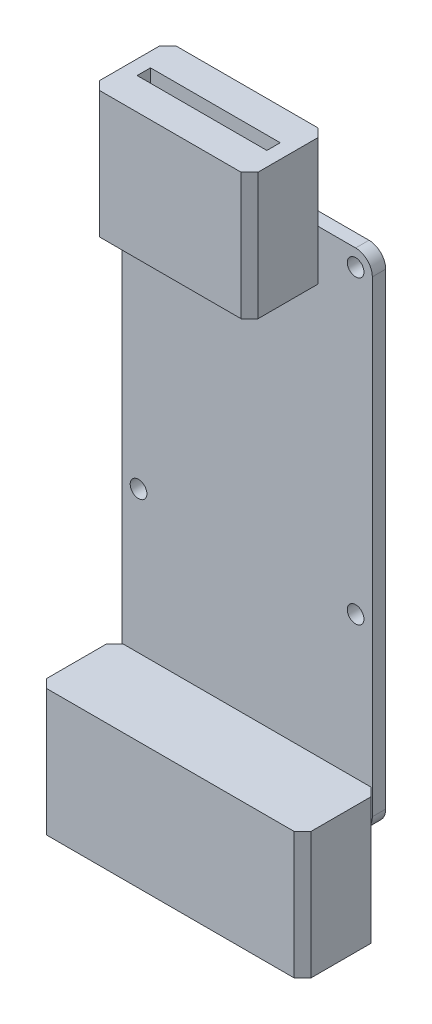
SolidWorks part; units mm, degrees
ref_plane "前视基准面" through (0, 0, 0) normal (0, 0, 1) x (1, 0, 0)
ref_plane "上视基准面" through (0, 0, 0) normal (0, 1, 0) x (1, 0, 0)
ref_plane "右视基准面" through (0, 0, 0) normal (1, 0, 0) x (0, 0, -1)
other "Configuration Table"
sketch "草图1" plane through (0, 0, 0) normal (0, 0, 1) x (1, 0, 0)
  line L1 (-13, 32.5) -> (13, 32.5)
  line L2 (-15, 30.5) -> (-15, -25.5)
  line L3 (-13, -27.5) -> (13, -27.5)
  line L4 (15, 30.5) -> (15, -25.5)
  arc A0 (-13, 32.5) -> (-15, 30.5) centre (-13, 30.5) ccw
  arc A1 (15, 30.5) -> (13, 32.5) centre (13, 30.5) ccw
  circle A2 centre (-13, 30.5) radius 1
  circle A3 centre (13, 30.5) radius 1
  arc A4 (-15, -25.5) -> (-13, -27.5) centre (-13, -25.5) ccw
  arc A5 (13, -27.5) -> (15, -25.5) centre (13, -25.5) ccw
  point P0 (0, 0)
  dimension "D3" = 4
  dimension "D4" = 4
  dimension "D5" = 2
  dimension "D6" = 2
  dimension "D7" = 4
  dimension "D8" = 4
  dimension "D9" = 60
  dimension "D10" = 30
  dimension "D11" = 32.5
  dimension "D12" = 15
extrude "凸台-拉伸1" add sketch "草图1" along normal blind 1.6
sketch "草图2" plane through (0, 0, 0) normal (0, 0, 1) x (1, 0, 0)
  line L0 (13, 32.5) -> (-13, 32.5) construction
  line L1 (-15, 32.5) -> (15, 32.5) construction
  line L2 (-15, 32.5) -> (-15, -7.5) construction
  line L3 (-15, -7.5) -> (15, -7.5) construction
  line L4 (15, 32.5) -> (15, -7.5) construction
  line L5 (-15, 30.5) -> (-15, -25.5) construction
  line L6 (15, -25.5) -> (15, 30.5) construction
  circle A0 centre (-13, -5.5) radius 2 construction
  circle A1 centre (13, -5.5) radius 2 construction
  circle A2 centre (-13, -5.5) radius 1
  circle A3 centre (13, -5.5) radius 1
  dimension "D2" = 4
  dimension "D3" = 4
  dimension "D4" = 2
  dimension "D5" = 2
  dimension "D1" = 40
extrude "切除-拉伸1" cut sketch "草图2" along normal blind 1.6
sketch "草图4" plane through (0, 0, 0) normal (0, 0, 1) x (1, 0, 0)
  line L0 (13, 32.5) -> (-13, 32.5) construction
  line L1 (-9.495, 42.7) -> (9.495, 42.7)
  line L2 (-9.495, 42.7) -> (-9.495, 27.5)
  line L3 (-9.495, 27.5) -> (9.495, 27.5)
  line L4 (9.495, 42.7) -> (9.495, 27.5)
  point P6 (0, 32.5)
  point P7 (0, 42.7)
  dimension "D1" = 18.99
  dimension "D2" = 5
  dimension "D3" = 15.2
extrude "凸台-拉伸2" add sketch "草图4" along normal blind 9.2 from surface at 1.6 starting at face at (-12, -5.5, 1.6)
sketch "草图5" plane through (0, 0, 0) normal (0, 1, 0) x (1, 0, 0)
  line L0 (-9.495, -10.8) -> (-8.495, -10.8)
  line L1 (-9.495, -10.8) -> (9.495, -10.8) construction
  line L2 (-8.495, -10.8) -> (-9.495, -9.8)
  line L3 (-9.495, -10.8) -> (-9.495, -1.6) construction
  line L4 (-9.495, -9.8) -> (-9.495, -10.8)
  line L5 (9.495, -10.8) -> (8.495, -10.8)
  line L6 (8.495, -10.8) -> (9.495, -9.8)
  line L7 (9.495, -10.8) -> (9.495, -1.6) construction
  line L8 (9.495, -9.8) -> (9.495, -10.8)
  line L9 (9.495, -1.6) -> (9.495, -2.6)
  line L10 (9.495, -2.6) -> (8.495, -1.6)
  line L11 (-9.495, -1.6) -> (9.495, -1.6) construction
  line L12 (8.495, -1.6) -> (9.495, -1.6)
  line L13 (-9.495, -1.6) -> (-8.495, -1.6)
  line L14 (-8.495, -1.6) -> (-9.495, -2.6)
  line L15 (-9.495, -2.6) -> (-9.495, -1.6)
  dimension "D1" = 1
  dimension "D2" = 1
  dimension "D3" = 1
  dimension "D4" = 1
  dimension "D5" = 1
  dimension "D6" = 1
  dimension "D7" = 1
extrude "切除-拉伸2" cut sketch "草图5" against normal up to surface (15.2 mm away) from surface at 42.7 up to face at (0, 27.5, 6.2) starting at face at (0, 42.7, 6.2)
sketch "草图6" plane through (0, 0, 0) normal (0, 1, 0) x (1, 0, 0)
  line L0 (9.495, -9.8) -> (9.495, -2.6) construction
  line L1 (-7.77, -5.4) -> (7.77, -5.4)
  line L2 (-7.77, -5.4) -> (-7.77, -7)
  line L3 (-7.77, -7) -> (7.77, -7)
  line L4 (7.77, -5.4) -> (7.77, -7)
  line L5 (8.495, -1.6) -> (-8.495, -1.6) construction
  point P6 (9.495, -6.2)
  point P7 (7.77, -6.2)
  point P10 (0, -1.6)
  point P11 (0, -5.4)
  dimension "D1" = 1.6
  dimension "D2" = 15.54
extrude "切除-拉伸3" cut sketch "草图6" against normal blind 9 from surface at 42.7 starting at face at (0, 42.7, 6.2)
sketch "草图7" plane through (0, 0, 0) normal (0, 0, 1) x (1, 0, 0)
  line L0 (-13, -27.5) -> (13, -27.5) construction
  line L1 (-15.845, -22.5) -> (15.845, -22.5)
  line L2 (-15.845, -22.5) -> (-15.845, -37.7)
  line L3 (-15.845, -37.7) -> (15.845, -37.7)
  line L4 (15.845, -22.5) -> (15.845, -37.7)
  point P6 (0, -27.5)
  point P7 (0, -22.5)
  dimension "D1" = 31.69
  dimension "D2" = 5
  dimension "D3" = 15.2
extrude "凸台-拉伸3" add sketch "草图7" along normal blind 9.2 from surface at 1.6 starting at face at (0, 11.6667, 1.6)
sketch "草图9" plane through (0, 0, 0) normal (0, 1, 0) x (1, 0, 0)
  line L0 (15.845, -10.8) -> (-15.845, -10.8) construction
  line L1 (-14.12, -7) -> (14.12, -7)
  line L2 (-14.12, -7) -> (-14.12, -5.4)
  line L3 (-14.12, -5.4) -> (14.12, -5.4)
  line L4 (14.12, -7) -> (14.12, -5.4)
  line L5 (-15.845, -10.8) -> (-15.845, -1.6) construction
  point P6 (0, -10.8)
  point P7 (0, -7)
  point P10 (-15.845, -6.2)
  point P11 (-14.12, -6.2)
  dimension "D1" = 28.24
  dimension "D2" = 1.6
extrude "切除-拉伸5" cut sketch "草图9" along normal blind 9 from surface at -37.7 starting at face at (0, -37.7, 6.2)
sketch "草图10" plane through (0, 0, 0) normal (0, 1, 0) x (1, 0, 0)
  line L0 (15.845, -10.8) -> (14.845, -10.8)
  line L1 (15.845, -10.8) -> (-15.845, -10.8) construction
  line L2 (14.845, -10.8) -> (15.845, -9.8)
  line L3 (15.845, -10.8) -> (15.845, -1.6) construction
  line L4 (15.845, -9.8) -> (15.845, -10.8)
  line L5 (-15.845, -10.8) -> (-14.845, -10.8)
  line L6 (-14.845, -10.8) -> (-15.845, -9.8)
  line L7 (-15.845, -10.8) -> (-15.845, -1.6) construction
  line L8 (-15.845, -9.8) -> (-15.845, -10.8)
  line L9 (-15.845, -2.6) -> (-14.845, -1.6)
  line L10 (-13, -1.6) -> (-15, -1.6) construction
  line L11 (-14.845, -1.6) -> (-15.845, -1.6)
  line L12 (-15.845, -1.6) -> (-15.845, -2.6)
  line L13 (15.845, -2.6) -> (14.845, -1.6)
  line L14 (-13, -1.6) -> (13, -1.6) construction
  line L15 (14.845, -1.6) -> (15.845, -1.6)
  line L16 (15.845, -1.6) -> (15.845, -2.6)
  dimension "D1" = 1
  dimension "D2" = 1
  dimension "D3" = 1
  dimension "D4" = 1
  dimension "D5" = 1
  dimension "D6" = 1
  dimension "D7" = 1
  dimension "D8" = 1
extrude "切除-拉伸6" cut sketch "草图10" along normal up to surface (15.2 mm away) from surface at -37.7 up to face at (0, -22.5, 4.6667) starting at face at (0, -37.7, 6.2)
